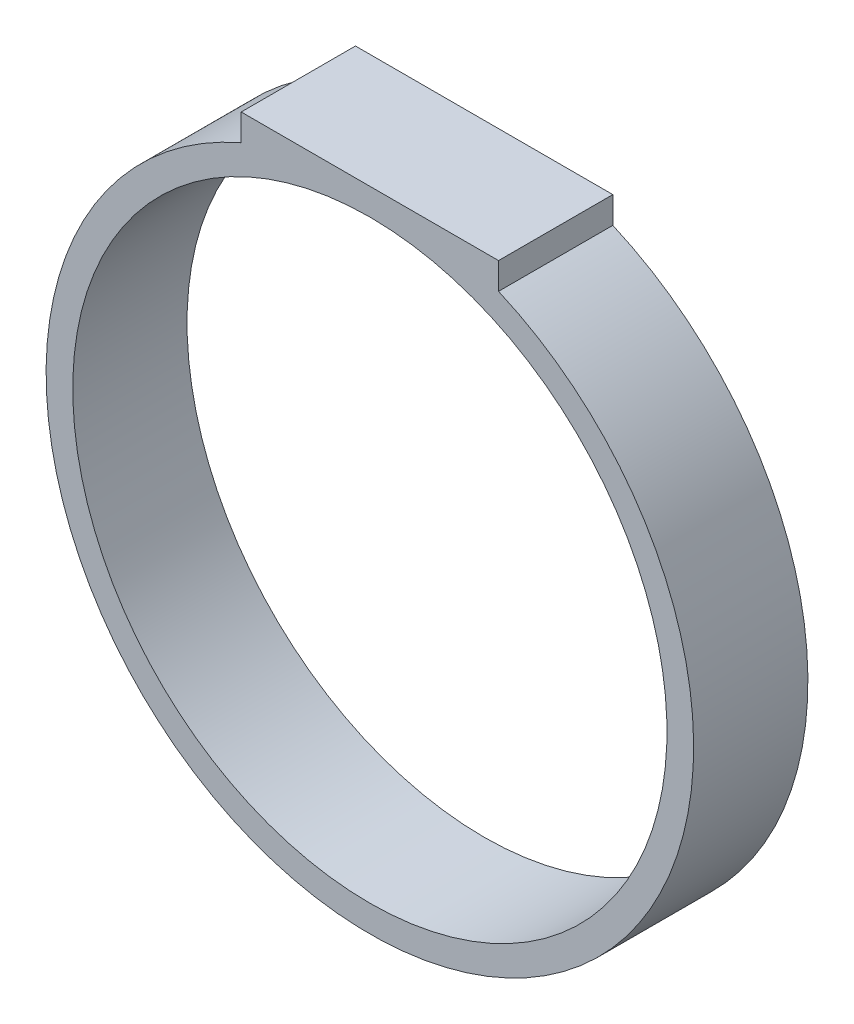
SolidWorks part; units mm, degrees
ref_plane "Ön Düzlem" through (0, 0, 0) normal (0, 0, 1) x (1, 0, 0)
ref_plane "Üst Düzlem" through (0, 0, 0) normal (0, 1, 0) x (1, 0, 0)
ref_plane "Sağ Düzlem" through (0, 0, 0) normal (1, 0, 0) x (0, 0, -1)
sketch "Çizim1" plane through (0, 0, 0) normal (0, 0, 1) x (1, 0, 0)
  circle A0 centre (0, 0) radius 78
  circle A1 centre (0, 0) radius 85
extrude "Yükseklik-Ekstrüzyon1" add sketch "Çizim1" along normal mid plane 30
sketch "Çizim2" plane through (0, 0, 15) normal (0, 0, 1) x (1, 0, 0)
  line L0 (-33.78, 85) -> (33.78, 85)
  line L2 (33.78, 77.9994) -> (-33.78, 77.9994)
  line L3 (-33.78, 77.9994) -> (-33.78, 85)
  line L5 (33.78, 77.9994) -> (33.78, 85)
  circle A0 centre (0, 0) radius 85 construction
extrude "Yükseklik-Ekstrüzyon2" add sketch "Çizim2" against normal blind 30
